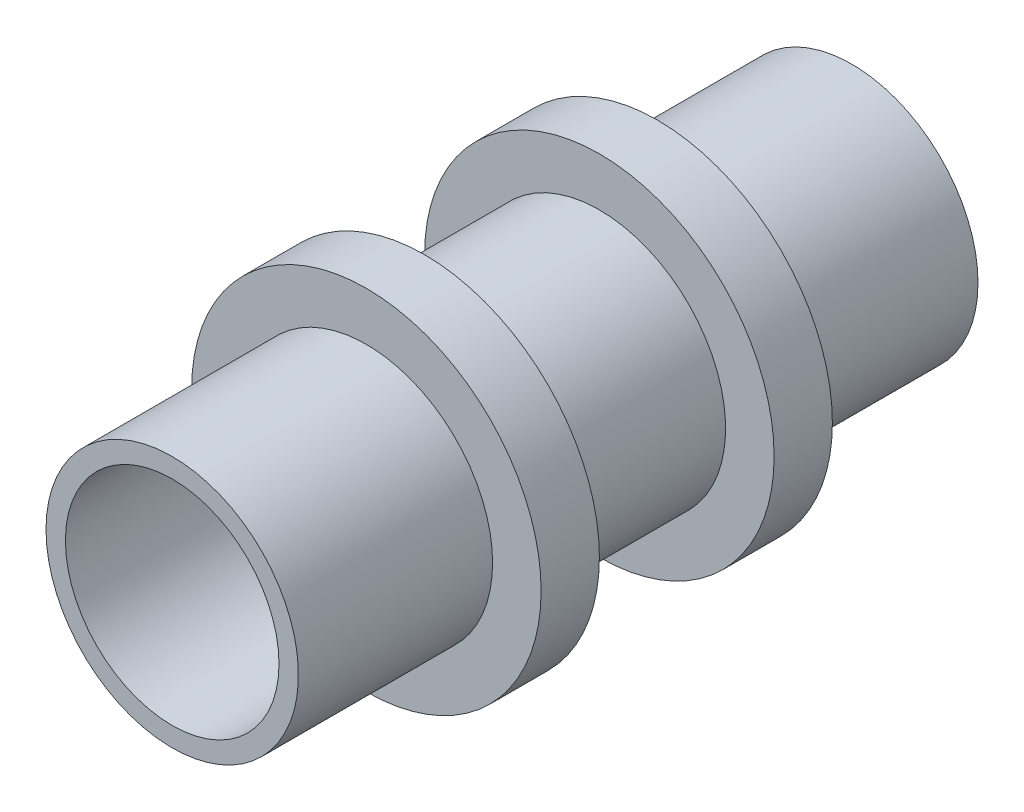
SolidWorks part; units mm, degrees
ref_plane "Front Plane" through (0, 0, 0) normal (0, 0, 1) x (1, 0, 0)
ref_plane "Top Plane" through (0, 0, 0) normal (0, 1, 0) x (1, 0, 0)
ref_plane "Right Plane" through (0, 0, 0) normal (1, 0, 0) x (0, 0, -1)
sketch "Sketch1" plane through (0, 0, 0) normal (0, 0, 1) x (1, 0, 0)
  circle A0 centre (0, 0) radius 8.255
  circle A2 centre (0, 0) radius 6.985
  dimension "D1" = 16.51
  dimension "D3" = 13.97
extrude "Boss-Extrude1" add sketch "Sketch1" along normal blind 19.05 contours A0 A2
sketch "Sketch2" plane through (0, 0, 0) normal (0, 0, 1) x (1, 0, 0)
  circle A0 centre (0, 0) radius 11.43
  circle A1 centre (0, 0) radius 8.255 construction
  circle A2 centre (0, 0) radius 8.255
  dimension "D1" = 22.86
extrude "Boss-Extrude2" add sketch "Sketch2" along normal blind 3.81
ref_plane "Plane1" through (0, 0, 9.525) normal (0, 0, -1) x (-1, 0, 0)
sketch "Sketch3" plane through (0, 0, 0) normal (0, 0, -1) x (-1, 0, 0)
  circle A0 centre (0, 0) radius 8.255 construction
  circle A1 centre (0, 0) radius 8.255
  circle A2 centre (0, 0) radius 6.985 construction
  circle A3 centre (0, 0) radius 6.985
extrude "Boss-Extrude3" add sketch "Sketch3" along normal blind 12.7
mirror "Mirror1" about plane through (0, 0, 9.525) normal (0, 0, -1) of "Boss-Extrude2"
mirror "Mirror2" about plane through (0, 0, 9.525) normal (0, 0, -1) of "Boss-Extrude3"
